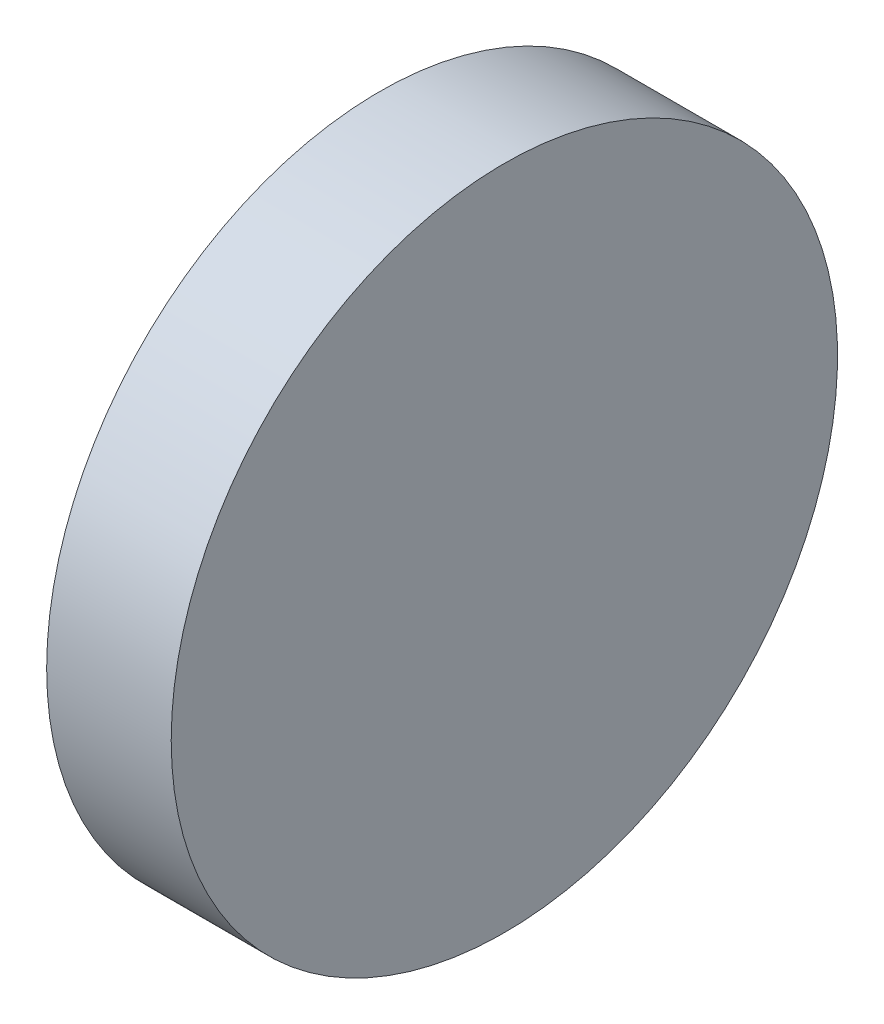
SolidWorks part; units mm, degrees
ref_plane "Front Plane" through (0, 0, 0) normal (0, 0, 1) x (1, 0, 0)
ref_plane "Top Plane" through (0, 0, 0) normal (0, 1, 0) x (1, 0, 0)
ref_plane "Right Plane" through (0, 0, 0) normal (1, 0, 0) x (0, 0, -1)
sketch "Sketch1" plane through (0, 0, 0) normal (1, 0, 0) x (0, 0, -1)
  circle A0 centre (0, 0) radius 12.7381
  dimension "D1" = 25.4762
extrude "Boss-Extrude1" add sketch "Sketch1" along normal blind 4.7625
